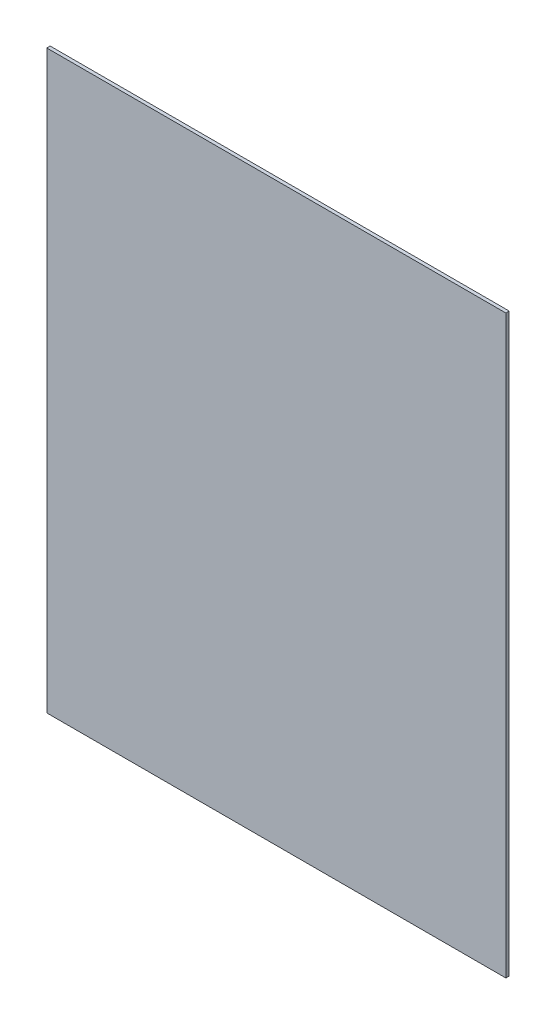
SolidWorks part; units mm, degrees
ref_plane "Front" through (0, 0, 0) normal (0, 0, 1) x (1, 0, 0)
ref_plane "Top" through (0, 0, 0) normal (0, 1, 0) x (1, 0, 0)
ref_plane "Right" through (0, 0, 0) normal (1, 0, 0) x (0, 0, -1)
sketch "Sketch1" plane through (0, 0, 0) normal (0, 0, 1) x (1, 0, 0)
  line L1 (0, 0) -> (430.276, 0)
  line L2 (0, 0) -> (0, 539.75)
  line L3 (0, 539.75) -> (430.276, 539.75)
  line L4 (430.276, 0) -> (430.276, 539.75)
  dimension "D1" = 539.75
  dimension "D2" = 430.276
extrude "Boss-Extrude1" add sketch "Sketch1" along normal blind 3.175
